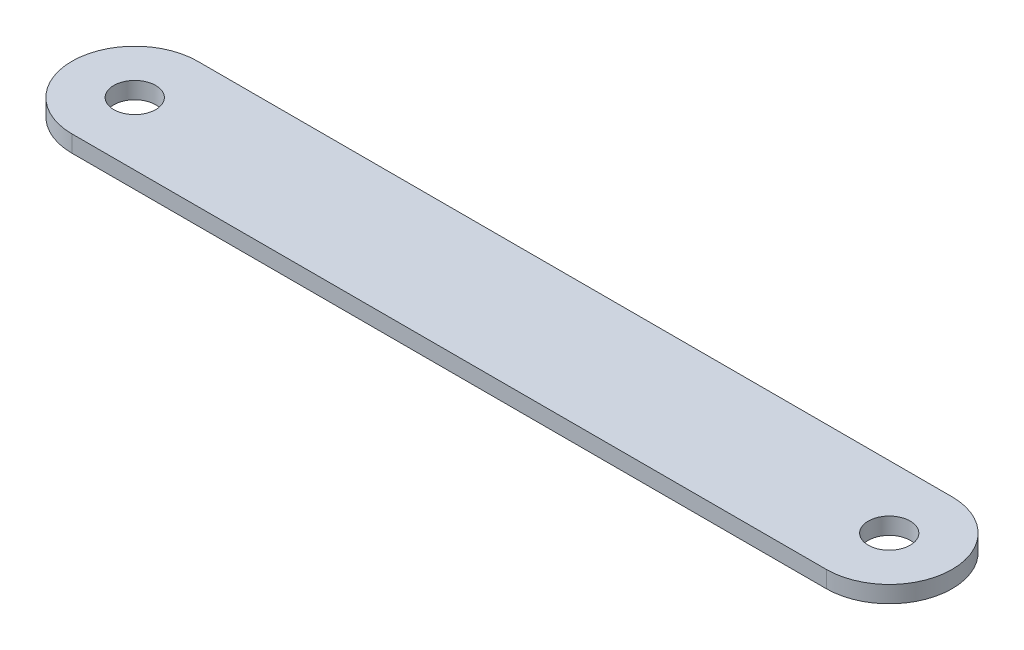
SolidWorks part; units mm, degrees
ref_plane "前视基准面" through (0, 0, 0) normal (0, 0, 1) x (1, 0, 0)
ref_plane "上视基准面" through (0, 0, 0) normal (0, 1, 0) x (1, 0, 0)
ref_plane "右视基准面" through (0, 0, 0) normal (1, 0, 0) x (0, 0, -1)
other "Configuration Table"
sketch "草图1" plane through (0, 0, 0) normal (0, 1, 0) x (1, 0, 0)
  line L0 (0, 0) -> (-180, 0) construction
  line L1 (0, -15) -> (-180, -15)
  line L2 (0, 15) -> (-180, 15)
  arc A0 (0, -15) -> (0, 15) centre (0, 0) ccw
  arc A1 (-180, 15) -> (-180, -15) centre (-180, 0) ccw
  point P3 (-90, 0)
  dimension "D1" = 15
  dimension "D2" = 180
extrude "凸台-拉伸1" add sketch "草图1" along normal blind 4
sketch "草图2" plane through (0, 4, 0) normal (0, 1, 0) x (1, 0, 0)
  circle A0 centre (0, 0) radius 5
  circle A1 centre (-180, 0) radius 5
  arc A2 (-180, 15) -> (-180, -15) centre (-180, 0) ccw construction
  dimension "D1" = 10
  dimension "D2" = 10
extrude "切除-拉伸1" cut sketch "草图2" against normal through all
